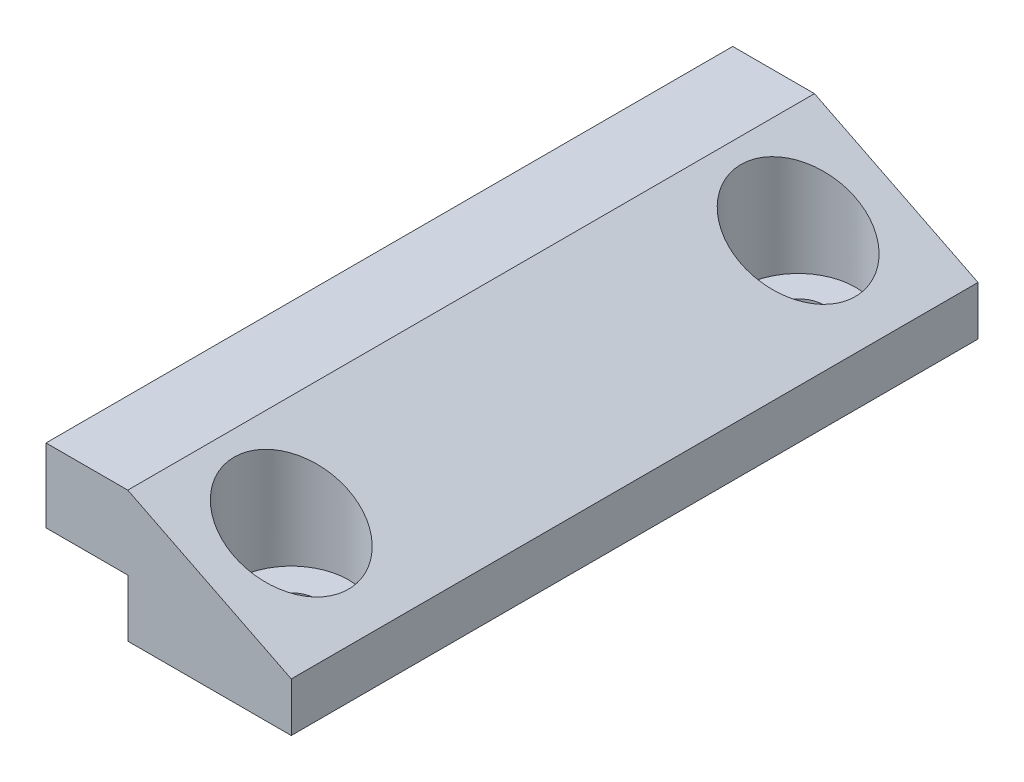
SolidWorks part; units mm, degrees
ref_plane "Plan de face" through (0, 0, 0) normal (0, 0, 1) x (1, 0, 0)
ref_plane "Plan de dessus" through (0, 0, 0) normal (0, 1, 0) x (1, 0, 0)
ref_plane "Plan de droite" through (0, 0, 0) normal (1, 0, 0) x (0, 0, -1)
sketch "Esquisse1" plane through (0, 0, 0) normal (0, 0, 1) x (1, 0, 0)
  line L0 (0, 3.5) -> (5, 3.5)
  line L1 (5, 0) -> (15, 0)
  line L2 (0, 3.5) -> (0, 8)
  line L3 (0, 8) -> (15, 8)
  line L4 (15, 0) -> (15, 8)
  line L5 (5, 3.5) -> (5, 0)
  dimension "D1" = 15
  dimension "D2" = 8
  dimension "D3" = 10
  dimension "D4" = 3.5
extrude "Boss.-Extru.1" add sketch "Esquisse1" along normal blind 42
sketch "Esquisse2" plane through (0, 8, 0) normal (0, 1, 0) x (1, 0, 0)
  line L1 (15, -42) -> (-27, -42) construction
  line L2 (15, -42) -> (15, 0) construction
  line L3 (15, 0) -> (-27, 0) construction
  line L4 (-27, -42) -> (-27, 0) construction
  circle A0 centre (9.5, -5.5) radius 2.5
  circle A1 centre (9.5, -36.5) radius 2.5
  dimension "D3" = 5
  dimension "D5" = 5
  dimension "D1" = 42
  dimension "D2" = 42
  dimension "D4" = 31
  dimension "D6" = 5.5
  dimension "D7" = 5.5
  dimension "D8" = 5.5
extrude "Enlèv. mat.-Extru.1" cut sketch "Esquisse2" against normal blind 42
sketch "Esquisse4" plane through (0, 8, 0) normal (0, 1, 0) x (1, 0, 0)
  circle A0 centre (9.5, -5.5) radius 3.5
  circle A1 centre (9.5, -36.5) radius 3.5
  dimension "D1" = 7
  dimension "D2" = 7
extrude "Enlèv. mat.-Extru.2" cut sketch "Esquisse4" against normal blind 8.5
sketch "Esquisse5" plane through (0, 0, 42) normal (0, 0, 1) x (1, 0, 0)
  line L1 (15, 8) -> (0, 8) construction
  line L2 (5, 8) -> (15, 3)
  line L3 (15, 0) -> (15, 8) construction
  line L4 (18.0541, 8.9629) -> (5.6264, 14.084)
  line L5 (5.6264, 14.084) -> (5, 8)
  line L6 (18.0541, 8.9629) -> (15, 3)
extrude "Enlèv. mat.-Extru.4" cut sketch "Esquisse5" against normal blind 47
sketch "Esquisse6" plane through (0, 0, 0) normal (0, -1, 0) x (-1, 0, 0)
  circle A0 centre (-9.5, -36.5) radius 3.5
  circle A1 centre (-9.5, -36.5) radius 1.5
  circle A2 centre (-9.5, -5.5) radius 3.5
  circle A3 centre (-9.5, -5.5) radius 1.6
  dimension "D1" = 3
  dimension "D2" = 3.2
extrude "Boss.-Extru.2" add sketch "Esquisse6" against normal blind 1
